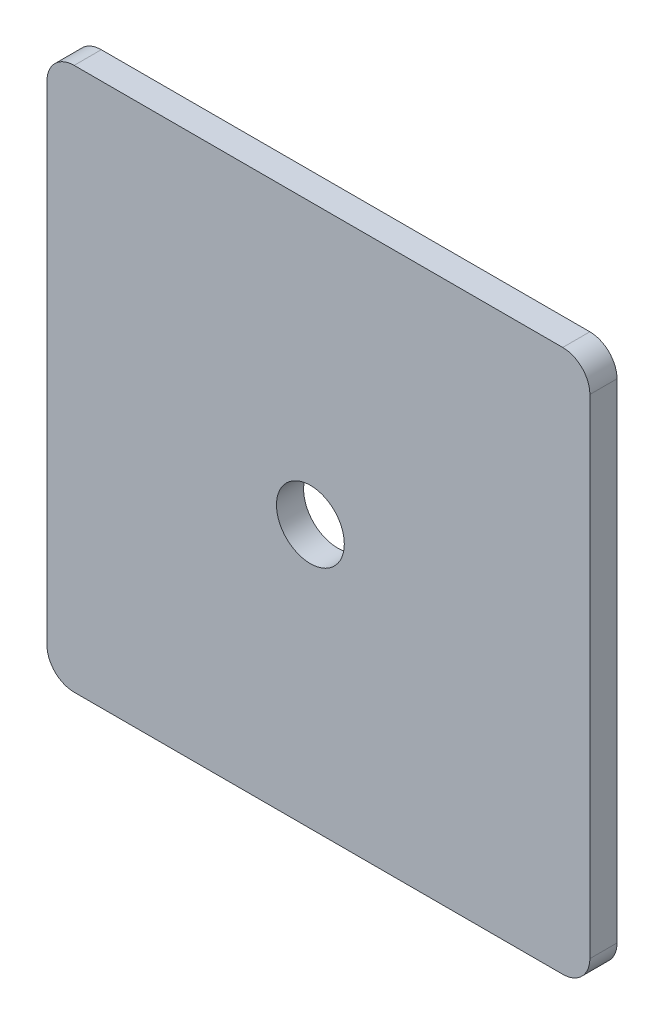
SolidWorks part; units mm, degrees
ref_plane "Plan de face" through (0, 0, 0) normal (0, 0, 1) x (1, 0, 0)
ref_plane "Plan de dessus" through (0, 0, 0) normal (0, 1, 0) x (1, 0, 0)
ref_plane "Plan de droite" through (0, 0, 0) normal (1, 0, 0) x (0, 0, -1)
sketch "Esquisse1" plane through (0, 0, 0) normal (0, 0, 1) x (1, 0, 0)
  line L1 (-90, -100) -> (90, -100)
  line L2 (-100, -90) -> (-100, 90)
  line L3 (-90, 100) -> (90, 100)
  line L4 (100, -90) -> (100, 90)
  line L5 (-100, -100) -> (100, 100) construction
  line L6 (-100, 100) -> (100, -100) construction
  arc A0 (-90, -100) -> (-100, -90) centre (-90, -90) cw
  arc A1 (90, -100) -> (100, -90) centre (90, -90) ccw
  arc A2 (100, 90) -> (90, 100) centre (90, 90) ccw
  arc A3 (-90, 100) -> (-100, 90) centre (-90, 90) ccw
  circle A4 centre (-2.9637, -2.9637) radius 12.5
  point P0 (0, 0)
  dimension "D3" = 10
  dimension "D4" = 25
  dimension "D1" = 200
  dimension "D2" = 200
extrude "Boss.-Extru.1" add sketch "Esquisse1" along normal blind 10
